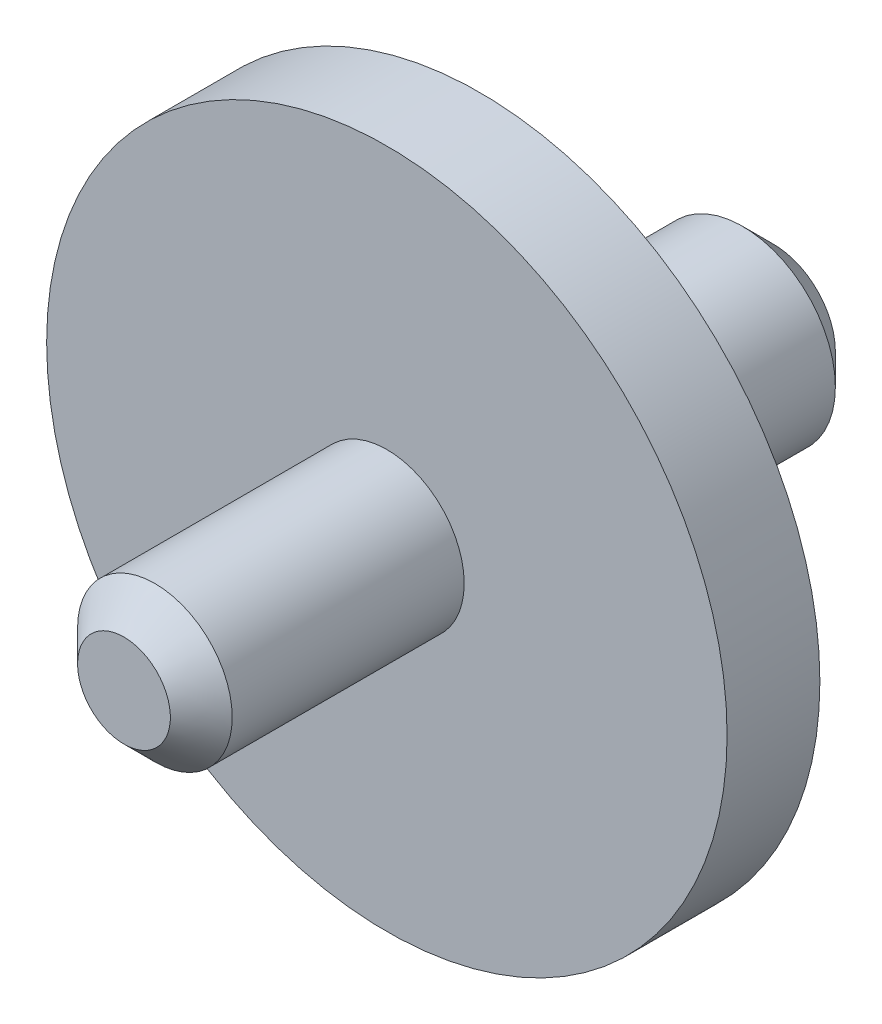
SolidWorks part; units mm, degrees
material "Alloy Steel"
ref_plane "Front Plane" through (0, 0, 0) normal (0, 0, 1) x (1, 0, 0)
ref_plane "Top Plane" through (0, 0, 0) normal (0, 1, 0) x (1, 0, 0)
ref_plane "Right Plane" through (0, 0, 0) normal (1, 0, 0) x (0, 0, -1)
sketch "Sketch1" plane through (0, 0, 0) normal (1, 0, 0) x (0, 0, -1)
  line L0 (-41.6195, 0) -> (49.0995, 0) construction
  line L1 (0, 0) -> (0, 2.5)
  line L2 (0, 2.5) -> (8.5, 2.5)
  line L3 (8.5, 2.5) -> (8.5, 11)
  line L4 (8.5, 11) -> (11.5, 11)
  line L5 (11.5, 11) -> (11.5, 5)
  line L6 (11.5, 5) -> (15.5, 5)
  line L7 (15.5, 5) -> (15.5, 3)
  line L8 (15.5, 3) -> (21, 3)
  line L9 (21, 3) -> (21, 0)
  line L10 (0, 0) -> (21, 0)
  dimension "D1" = 8.5
  dimension "D2" = 2.5
  dimension "D3" = 11
  dimension "D4" = 6
  dimension "D5" = 3
  dimension "D6" = 4
  dimension "D7" = 3
  dimension "D8" = 5.5
revolve "Revolve1" add sketch "Sketch1" angle 360 about L0
chamfer "Chamfer1" distance 1 angle 45 2 edges at (2.5, 0, 0) (3, 0, -21)
